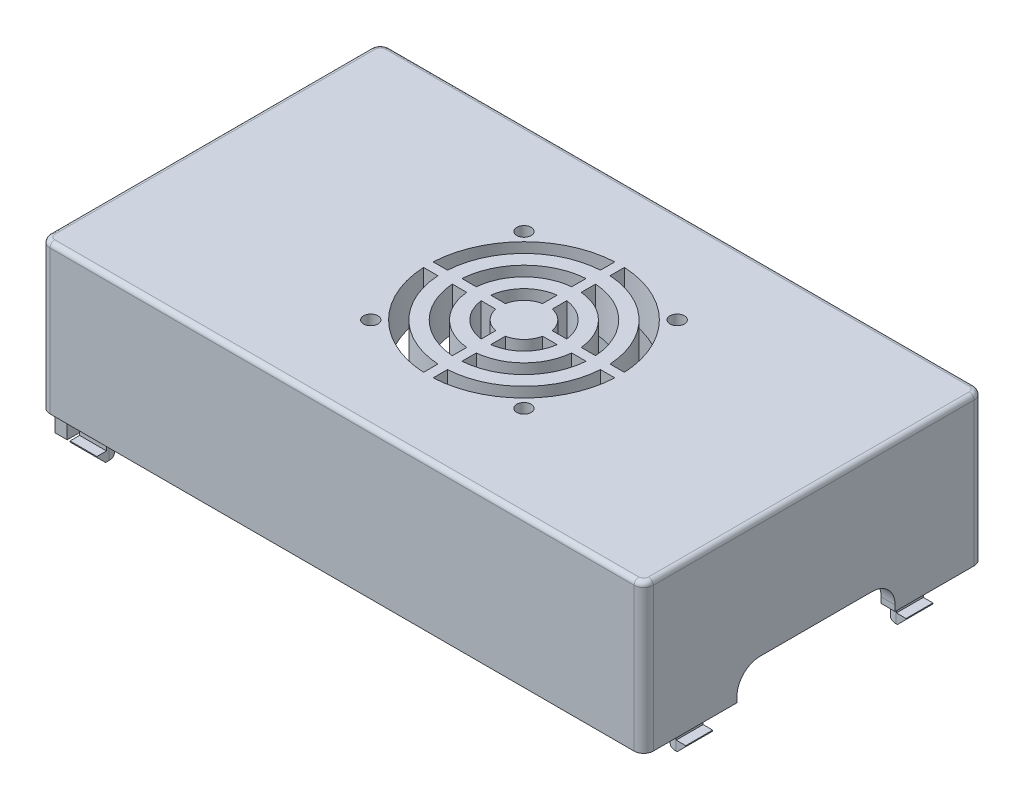
SolidWorks part; units mm, degrees
material "ABS"
ref_plane "Front Plane" through (0, 0, 0) normal (0, 0, 1) x (1, 0, 0)
ref_plane "Top Plane" through (0, 0, 0) normal (0, 1, 0) x (1, 0, 0)
ref_plane "Right Plane" through (0, 0, 0) normal (1, 0, 0) x (0, 0, -1)
sketch "Sketch1" plane through (0, 0, 0) normal (0, 1, 0) x (1, 0, 0)
  line L1 (-63, -35.5) -> (63, -35.5)
  line L2 (-63, -35.5) -> (-63, 35.5)
  line L3 (-63, 35.5) -> (63, 35.5)
  line L4 (63, -35.5) -> (63, 35.5)
  line L5 (-63, -35.5) -> (63, 35.5) construction
  line L6 (-63, 35.5) -> (63, -35.5) construction
  point P0 (0, 0)
  dimension "D1" = 126
  dimension "D2" = 71
extrude "Boss-Extrude1" add sketch "Sketch1" along normal blind 31
sketch "Sketch2" plane through (0, 0, 0) normal (0, -1, 0) x (1, 0, 0)
  line L0 (63, 35.5) -> (63, -35.5) construction
  line L1 (-60.5, 33) -> (60.1, 33)
  line L2 (-60.5, 33) -> (-60.5, -33)
  line L3 (-60.5, -33) -> (60.1, -33)
  line L4 (60.1, 33) -> (60.1, -33)
  line L5 (-63, 35.5) -> (63, 35.5) construction
  line L6 (63, -35.5) -> (-63, -35.5) construction
  line L7 (-63, -35.5) -> (-63, 35.5) construction
  dimension "D1" = 2.9
  dimension "D2" = 2.5
  dimension "D3" = 2.5
  dimension "D4" = 2.5
extrude "Cut-Extrude1" cut sketch "Sketch2" against normal blind 22
sketch "Sketch3" plane through (63, 0, 0) normal (1, 0, 0) x (0, 0, -1)
  line L0 (-35.5, 0) -> (35.5, 0) construction
  line L1 (-16, 0) -> (17, 0)
  line L2 (-16, 0) -> (-16, 6)
  line L3 (-16, 6) -> (17, 6)
  line L4 (17, 0) -> (17, 6)
  line L5 (-35.5, 31) -> (-35.5, 0) construction
  dimension "D1" = 33
  dimension "D2" = 6
  dimension "D3" = 19.5
extrude "Cut-Extrude2" cut sketch "Sketch3" against normal up to next
fillet "Fillet1" radius 4.8 2 edges at (61.55, 6, -17) (61.55, 6, 16)
sketch "Sketch4" plane through (-63, 0, 0) normal (-1, 0, 0) x (0, 0, 1)
  line L0 (-35.5, 31) -> (-35.5, 0) construction
  line L1 (-35.5, 0) -> (35.5, 0) construction
  line L2 (-32.6, 0) -> (-32.6, -19)
  line L3 (-32.6, -19) -> (5, -19)
  line L4 (5, -19) -> (5, -6)
  line L5 (5, -6) -> (32.4, -6)
  line L6 (32.4, -6) -> (32.4, 0)
  line L7 (33, 0) -> (-33, 0) construction
  line L8 (32.4, 0) -> (-32.6, 0)
  line L9 (35.5, 31) -> (35.5, 0) construction
  dimension "D1" = 19
  dimension "D2" = 37.6
  dimension "D3" = 13
  dimension "D4" = 2.9
  dimension "D5" = 3.1
extrude "Boss-Extrude2" add sketch "Sketch4" against normal up to surface (2.5 mm away) up to face at (-60.5, 11, 0)
sketch "Sketch5" plane through (0, 31, 0) normal (0, 1, 0) x (1, 0, 0)
  line L0 (2.5, 0) -> (22.5, 0) construction
  line L1 (2.5, 0) -> (-31.6667, 0) construction
  line L2 (2.5, 0) -> (2.5, 20) construction
  line L3 (2.5, 0) -> (2.5, -20) construction
  line L4 (3.5, 4.899) -> (3.5, 7.9373)
  line L5 (1.5, -4.899) -> (1.5, -7.9373)
  line L6 (7.399, -1) -> (10.4373, -1)
  line L7 (-2.399, 1) -> (-5.4373, 1)
  line L8 (1.5, 4.899) -> (1.5, 7.9373)
  line L9 (3.5, -4.899) -> (3.5, -7.9373)
  line L10 (7.399, 1) -> (10.4373, 1)
  line L11 (-2.399, -1) -> (-5.4373, -1)
  line L12 (1.5, 0) -> (1.5, 23.1605) construction
  line L13 (2.5, 1) -> (-36.7284, 1) construction
  line L14 (2.5, 1) -> (10.6296, 1) construction
  line L15 (3.5, 0) -> (3.5, 23.1605) construction
  line L16 (3.5, 0) -> (3.5, -24.7161) construction
  line L17 (2.5, -1) -> (10.6296, -1) construction
  line L18 (2.5, -1) -> (-36.7284, -1) construction
  line L19 (1.5, 0) -> (1.5, -24.7161) construction
  line L20 (2.5, 0) -> (2.5, -24.7161) construction
  line L21 (2.5, 0) -> (10.6296, 0) construction
  line L22 (2.5, 0) -> (2.5, 23.1605) construction
  line L23 (2.5, 0) -> (-36.7284, 0) construction
  line L24 (1.5, 10.9545) -> (1.5, 13.9642)
  line L25 (1.5, 16.9706) -> (1.5, 19.975)
  line L26 (3.5, 16.9706) -> (3.5, 19.975)
  line L27 (3.5, 10.9545) -> (3.5, 13.9642)
  line L28 (-8.4545, -1) -> (-11.4642, -1)
  line L29 (-8.4545, 1) -> (-11.4642, 1)
  line L30 (-14.4706, -1) -> (-17.475, -1)
  line L31 (-14.4706, 1) -> (-17.475, 1)
  line L32 (1.5, -10.9545) -> (1.5, -13.9642)
  line L33 (3.5, -10.9545) -> (3.5, -13.9642)
  line L34 (3.5, -16.9706) -> (3.5, -19.975)
  line L35 (1.5, -16.9706) -> (1.5, -19.975)
  line L36 (13.4545, -1) -> (16.4642, -1)
  line L37 (13.4545, 1) -> (16.4642, 1)
  line L38 (19.4706, 1) -> (22.475, 1)
  line L39 (19.4706, -1) -> (22.475, -1)
  line L40 (63, 35.5) -> (-63, 35.5) construction
  line L41 (-63, 35.5) -> (-63, -35.5) construction
  arc A0 (-17.475, -1) -> (1.5, -19.975) centre (2.5, 0) ccw
  arc A1 (-11.4642, -1) -> (1.5, -13.9642) centre (2.5, 0) ccw
  arc A2 (-5.4373, -1) -> (1.5, -7.9373) centre (2.5, 0) ccw
  arc A3 (-14.4706, -1) -> (1.5, -16.9706) centre (2.5, 0) ccw
  arc A4 (-8.4545, -1) -> (1.5, -10.9545) centre (2.5, 0) ccw
  arc A5 (-2.399, -1) -> (1.5, -4.899) centre (2.5, 0) ccw
  circle A6 centre (2.5, 0) radius 20 construction
  circle A7 centre (2.5, 0) radius 17 construction
  circle A8 centre (2.5, 0) radius 14 construction
  circle A9 centre (2.5, 0) radius 11 construction
  circle A10 centre (2.5, 0) radius 8 construction
  circle A11 centre (2.5, 0) radius 5 construction
  arc A12 (22.475, 1) -> (3.5, 19.975) centre (2.5, 0) ccw
  arc A13 (19.4706, 1) -> (3.5, 16.9706) centre (2.5, 0) ccw
  arc A14 (16.4642, 1) -> (3.5, 13.9642) centre (2.5, 0) ccw
  arc A15 (13.4545, 1) -> (3.5, 10.9545) centre (2.5, 0) ccw
  arc A16 (10.4373, 1) -> (3.5, 7.9373) centre (2.5, 0) ccw
  arc A17 (7.399, 1) -> (3.5, 4.899) centre (2.5, 0) ccw
  arc A18 (3.5, -19.975) -> (22.475, -1) centre (2.5, 0) ccw
  arc A19 (3.5, -16.9706) -> (19.4706, -1) centre (2.5, 0) ccw
  arc A20 (3.5, -13.9642) -> (16.4642, -1) centre (2.5, 0) ccw
  arc A21 (3.5, -10.9545) -> (13.4545, -1) centre (2.5, 0) ccw
  arc A22 (3.5, -7.9373) -> (10.4373, -1) centre (2.5, 0) ccw
  arc A23 (3.5, -4.899) -> (7.399, -1) centre (2.5, 0) ccw
  arc A24 (1.5, 4.899) -> (-2.399, 1) centre (2.5, 0) ccw
  arc A25 (1.5, 7.9373) -> (-5.4373, 1) centre (2.5, 0) ccw
  arc A26 (1.5, 10.9545) -> (-8.4545, 1) centre (2.5, 0) ccw
  arc A27 (1.5, 13.9642) -> (-11.4642, 1) centre (2.5, 0) ccw
  arc A28 (1.5, 19.975) -> (-17.475, 1) centre (2.5, 0) ccw
  arc A29 (1.5, 16.9706) -> (-14.4706, 1) centre (2.5, 0) ccw
  dimension "D1" = 40
  dimension "D2" = 28
  dimension "D3" = 16
  dimension "D9" = 35.5
  dimension "D10" = 65.5
  dimension "D4" = 3
  dimension "D5" = 3
  dimension "D6" = 3
  dimension "D7" = 1
  dimension "D8" = 1
extrude "Cut-Extrude3" cut sketch "Sketch5" against normal through all
sketch "Sketch6" plane through (0, 31, 0) normal (0, 1, 0) x (1, 0, 0)
  line L0 (-13.5, 16) -> (18.5, 16) construction
  line L1 (18.5, 16) -> (18.5, -16) construction
  line L2 (2.5, 0) -> (2.5, -8.916) construction
  line L3 (-13.5, 16) -> (18.5, -16) construction
  circle A0 centre (-13.5, 16) radius 1.5
  circle A1 centre (18.5, 16) radius 1.5
  circle A2 centre (18.5, -16) radius 1.5
  circle A3 centre (-13.5, -16) radius 1.5
  dimension "D1" = 3
  dimension "D2" = 32
extrude "Cut-Extrude4" cut sketch "Sketch6" against normal through all
fillet "Fillet2" radius 2 4 edges at (-63, 15.5, 35.5) (-63, 15.5, -35.5) (63, 15.5, -35.5) (63, 15.5, 35.5)
fillet "Fillet3" radius 1 8 edges at (-62.4142, 31, 34.9142) (-63, 31, 0) (-62.4142, 31, -34.9142) (0, 31, -35.5) (62.4142, 31, -34.9142) (63, 31, 0) (62.4142, 31, 34.9142) (0, 31, 35.5)
sketch "Sketch7" plane through (0, 0, 0) normal (0, -1, 0) x (1, 0, 0)
  line L0 (63, 33.5) -> (63, 16) construction
  line L1 (-61, 35.5) -> (61, 35.5) construction
  line L2 (61, -35.5) -> (-61, -35.5) construction
  line L3 (57.1993, 23) -> (57.1993, -23) construction
  line L4 (0, 0) -> (57.1993, 0) construction
  line L5 (-63, 5) -> (-63, 32.4) construction
  line L6 (-57.3138, 32.513) -> (-57.3138, 33)
  line L8 (-57.3138, 33) -> (-51.6862, 33)
  line L11 (-51.6862, 32.513) -> (-51.6862, 33)
  line L12 (60.1, 33) -> (-60.5, 33) construction
  line L13 (-57.3138, -32.513) -> (-57.3138, -33)
  line L14 (-57.3138, -33) -> (-51.6862, -33)
  line L16 (-51.6862, -32.513) -> (-51.6862, -33)
  line L17 (-60.5, -33) -> (60.1, -33) construction
  line L18 (60.013, -25.8138) -> (60.1, -25.8138)
  line L19 (60.013, -20.1862) -> (60.1, -20.1862)
  line L20 (60.1, -20.1862) -> (60.1, -25.8138)
  line L22 (60.1, -33) -> (60.1, -17) construction
  line L23 (60.013, 25.8138) -> (60.1, 25.8138)
  line L24 (60.1, 25.8138) -> (60.1, 20.1862)
  line L26 (60.013, 20.1862) -> (60.1, 20.1862)
  line L27 (60.1, 16) -> (60.1, 33) construction
  arc A0 (-57.3138, 32.513) -> (-51.6862, 32.513) centre (-54.5, 32.513) ccw
  arc A1 (-51.6862, -32.513) -> (-57.3138, -32.513) centre (-54.5, -32.513) ccw
  arc A2 (60.013, 25.8138) -> (60.013, 20.1862) centre (60.013, 23) ccw
  arc A3 (60.013, -20.1862) -> (60.013, -25.8138) centre (60.013, -23) ccw
  dimension "D1" = 5.6275
  dimension "D3" = 2.987
  dimension "D4" = 2.987
  dimension "D5" = 46
  dimension "D6" = 8.5
  dimension "D2" = 2.987
extrude "Boss-Extrude3" add sketch "Sketch7" against normal blind 4.7
sketch "Sketch8" plane through (0, 0, 0) normal (0, -1, 0) x (1, 0, 0)
  line L0 (-57.3138, 33) -> (-57.3138, 32.513) construction
  line L1 (-57.3138, -32.513) -> (-57.3138, -33) construction
  line L2 (60.013, 20.1862) -> (60.1, 20.1862) construction
  line L3 (60.013, -25.8138) -> (60.1, -25.8138) construction
  line L4 (-51.6862, 32.513) -> (-51.6862, 33) construction
  line L5 (-57.3138, 33) -> (-57.3138, 32.513)
  line L6 (-51.6862, 32.513) -> (-51.6862, 33)
  line L7 (-57.3138, 33) -> (-51.6862, 33)
  line L8 (-51.6862, -33) -> (-51.6862, -32.513) construction
  line L9 (-57.3138, -32.513) -> (-57.3138, -33)
  line L10 (-51.6862, -33) -> (-51.6862, -32.513)
  line L11 (-57.3138, -33) -> (-51.6862, -33)
  line L12 (60.1, -20.1862) -> (60.013, -20.1862) construction
  line L13 (60.013, -25.8138) -> (60.1, -25.8138)
  line L14 (60.1, -20.1862) -> (60.013, -20.1862)
  line L15 (60.1, -20.1862) -> (60.1, -25.8138)
  line L16 (60.1, 25.8138) -> (60.013, 25.8138) construction
  line L17 (60.013, 20.1862) -> (60.1, 20.1862)
  line L18 (60.1, 25.8138) -> (60.013, 25.8138)
  line L19 (60.1, 25.8138) -> (60.1, 20.1862)
  arc A0 (-57.3138, 32.513) -> (-51.6862, 32.513) centre (-54.5, 32.513) ccw construction
  arc A1 (-57.3138, 32.513) -> (-51.6862, 32.513) centre (-54.5, 32.513) ccw
  arc A2 (-51.6862, -32.513) -> (-57.3138, -32.513) centre (-54.5, -32.513) ccw construction
  arc A3 (-51.6862, -32.513) -> (-57.3138, -32.513) centre (-54.5, -32.513) ccw
  arc A4 (60.013, -20.1862) -> (60.013, -25.8138) centre (60.013, -23) ccw construction
  arc A5 (60.013, 25.8138) -> (60.013, 20.1862) centre (60.013, 23) ccw construction
  arc A6 (60.013, -20.1862) -> (60.013, -25.8138) centre (60.013, -23) ccw
  arc A7 (60.013, 25.8138) -> (60.013, 20.1862) centre (60.013, 23) ccw
extrude "Boss-Extrude4" add sketch "Sketch8" along normal blind 5.3
sketch "Sketch9" plane through (0, 0, 0) normal (1, 0, 0) x (0, 0, -1)
  line L0 (-33, 4.7) -> (-29.6993, 1.3993)
  line L1 (-29.6993, -5.3) -> (-29.6993, 4.7) construction
  line L2 (-29.6993, 1.3993) -> (-29.6993, 4.7)
  line L3 (-29.6993, 4.7) -> (-33, 4.7)
  line L4 (33, 4.7) -> (29.6993, 1.3993)
  line L5 (29.6993, 4.7) -> (29.6993, -5.3) construction
  line L6 (29.6993, 1.3993) -> (29.6993, 4.7)
  line L7 (29.6993, 4.7) -> (33, 4.7)
  dimension "D1" = 45
extrude "Cut-Extrude5" cut sketch "Sketch9" against normal up to surface (60.5 mm away) up to face at (-60.5, -1.25, 1.01)
sketch "Sketch10" plane through (0, 0, -33) normal (0, 0, 1) x (1, 0, 0)
  line L0 (60.1, 4.7) -> (57.1993, 1.7993)
  line L1 (57.1993, 4.7) -> (57.1993, -5.3) construction
  line L2 (57.1993, 1.7993) -> (57.1993, 4.7)
  line L3 (57.1993, 4.7) -> (60.1, 4.7)
extrude "Cut-Extrude6" cut sketch "Sketch10" along normal up to surface (66 mm away) up to face at (-27.35, 6.675, 33)
sketch "Sketch11" plane through (0, 0, 25.8138) normal (0, 0, 1) x (1, 0, 0)
  line L0 (60.1, -3.3) -> (62.1, -3.3)
  line L1 (60.1, -5.3) -> (60.1, 0) construction
  line L2 (62.1, -3.3) -> (62.1, -3.5)
  line L3 (62.1, -3.5) -> (60.3, -5.3)
  line L4 (60.3, -5.3) -> (60.1, -5.3)
  line L5 (60.1, -5.3) -> (60.1, -3.3)
  line L6 (61, 0) -> (63, 0) construction
  dimension "D1" = 2
  dimension "D2" = 0.2
  dimension "D3" = 3.3
  dimension "D4" = 0.2
extrude "Boss-Extrude5" add sketch "Sketch11" against normal up to surface (5.6275 mm away) up to face at (60.0652, -0.2574, 20.1862)
sketch "Sketch12" plane through (0, 0, -20.1862) normal (0, 0, 1) x (1, 0, 0)
  line L0 (60.1, -3.3) -> (62.1, -3.3)
  line L1 (62.1, -3.3) -> (62.1, -3.5)
  line L2 (62.1, -3.5) -> (60.3, -5.3)
  line L3 (60.3, -5.3) -> (60.1, -5.3)
  line L5 (60.1, -3.3) -> (60.1, -5.3)
extrude "Boss-Extrude6" add sketch "Sketch12" against normal up to surface (5.6275 mm away) up to face at (60.0652, -0.2574, -25.8138)
sketch "Sketch13" plane through (-51.6862, 0, 0) normal (1, 0, 0) x (0, 0, -1)
  line L0 (-33, -3.3) -> (-35, -3.3)
  line L1 (-33, -5.3) -> (-33, 0) construction
  line L2 (-35, -3.3) -> (-35, -3.5)
  line L3 (-35, -3.5) -> (-33.2, -5.3)
  line L4 (-33.2, -5.3) -> (-33, -5.3)
  line L5 (-33, -5.3) -> (-33, -3.3)
  line L6 (-35.5, 0) -> (-33.5, 0) construction
  line L7 (33, -5.3) -> (33.2, -5.3)
  line L8 (33.2, -5.3) -> (35, -3.5)
  line L9 (35, -3.5) -> (35, -3.3)
  line L10 (35, -3.3) -> (33, -3.3)
  line L11 (33, -5.3) -> (33, 0) construction
  line L12 (33, -3.3) -> (33, -5.3)
  dimension "D1" = 0.2
  dimension "D2" = 0.2
  dimension "D3" = 3.3
  dimension "D4" = 2
extrude "Boss-Extrude7" add sketch "Sketch13" against normal up to surface (5.6275 mm away) up to face at (-57.3138, -0.3374, -32.8052)
